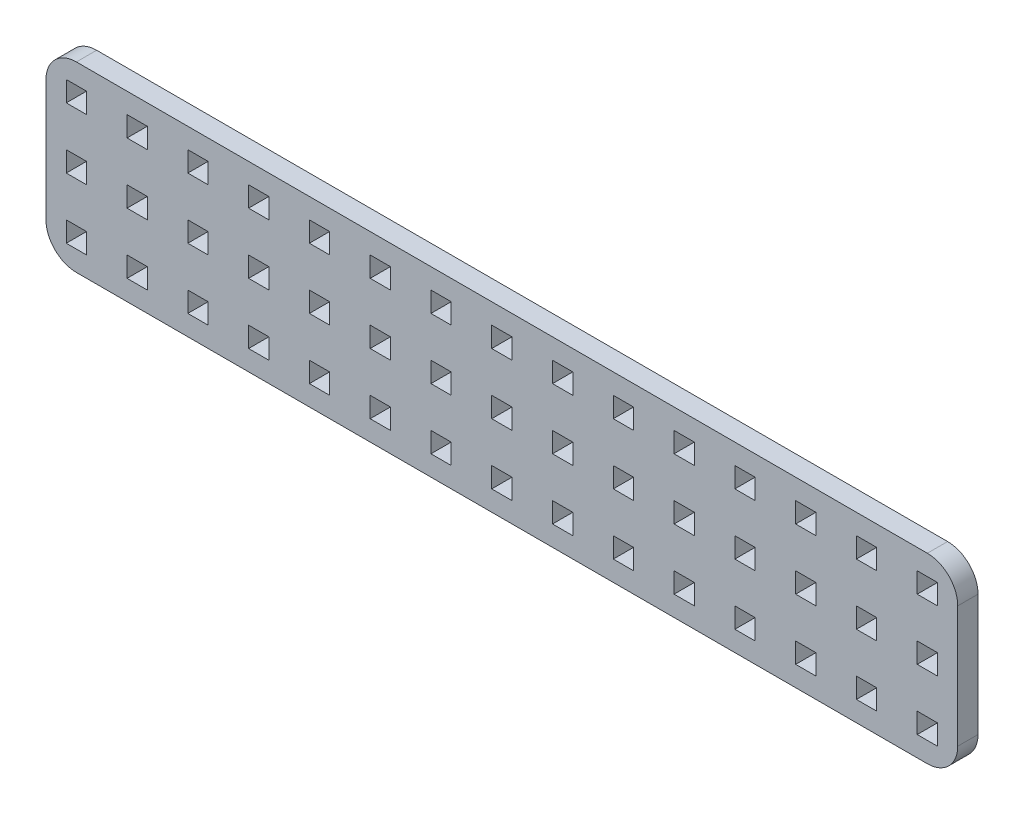
SolidWorks part; units mm, degrees
ref_plane "Alzado" through (0, 0, 0) normal (0, 0, 1) x (1, 0, 0)
ref_plane "Planta" through (0, 0, 0) normal (0, 1, 0) x (1, 0, 0)
ref_plane "Vista lateral" through (0, 0, 0) normal (1, 0, 0) x (0, 0, -1)
sketch "Model" plane through (0, 0, 0) normal (0, 0, 1) x (1, 0, 0)
  line L0 (7.8927, 294.0684) -> (7.8927, 291.0684)
  line L1 (10.8927, 294.0684) -> (7.8927, 294.0684)
  line L2 (10.8927, 291.0684) -> (10.8927, 294.0684)
  line L3 (7.8927, 291.0684) -> (10.8927, 291.0684)
  line L4 (16.8927, 294.0684) -> (16.8927, 291.0684)
  line L5 (19.8927, 294.0684) -> (16.8927, 294.0684)
  line L6 (19.8927, 291.0684) -> (19.8927, 294.0684)
  line L7 (16.8927, 291.0684) -> (19.8927, 291.0684)
  line L8 (25.8927, 294.0684) -> (25.8927, 291.0684)
  line L9 (28.8927, 294.0684) -> (25.8927, 294.0684)
  line L10 (28.8927, 291.0684) -> (28.8927, 294.0684)
  line L11 (25.8927, 291.0684) -> (28.8927, 291.0684)
  line L12 (34.8927, 294.0684) -> (34.8927, 291.0684)
  line L13 (37.8927, 294.0684) -> (34.8927, 294.0684)
  line L14 (37.8927, 291.0684) -> (37.8927, 294.0684)
  line L15 (34.8927, 291.0684) -> (37.8927, 291.0684)
  line L16 (43.8927, 294.0684) -> (43.8927, 291.0684)
  line L17 (46.8927, 294.0684) -> (43.8927, 294.0684)
  line L18 (46.8927, 291.0684) -> (46.8927, 294.0684)
  line L19 (43.8927, 291.0684) -> (46.8927, 291.0684)
  line L20 (52.8927, 294.0684) -> (52.8927, 291.0684)
  line L21 (55.8927, 294.0684) -> (52.8927, 294.0684)
  line L22 (55.8927, 291.0684) -> (55.8927, 294.0684)
  line L23 (52.8927, 291.0684) -> (55.8927, 291.0684)
  line L24 (61.8927, 294.0684) -> (61.8927, 291.0684)
  line L25 (64.8927, 294.0684) -> (61.8927, 294.0684)
  line L26 (64.8927, 291.0684) -> (64.8927, 294.0684)
  line L27 (61.8927, 291.0684) -> (64.8927, 291.0684)
  line L28 (70.8927, 294.0684) -> (70.8927, 291.0684)
  line L29 (73.8927, 294.0684) -> (70.8927, 294.0684)
  line L30 (73.8927, 291.0684) -> (73.8927, 294.0684)
  line L31 (70.8927, 291.0684) -> (73.8927, 291.0684)
  line L32 (79.8927, 294.0684) -> (79.8927, 291.0684)
  line L33 (82.8927, 294.0684) -> (79.8927, 294.0684)
  line L34 (82.8927, 291.0684) -> (82.8927, 294.0684)
  line L35 (79.8927, 291.0684) -> (82.8927, 291.0684)
  line L36 (88.8927, 294.0684) -> (88.8927, 291.0684)
  line L37 (91.8927, 294.0684) -> (88.8927, 294.0684)
  line L38 (91.8927, 291.0684) -> (91.8927, 294.0684)
  line L39 (88.8927, 291.0684) -> (91.8927, 291.0684)
  line L40 (97.8927, 294.0684) -> (97.8927, 291.0684)
  line L41 (100.8927, 294.0684) -> (97.8927, 294.0684)
  line L42 (100.8927, 291.0684) -> (100.8927, 294.0684)
  line L43 (97.8927, 291.0684) -> (100.8927, 291.0684)
  line L44 (106.8927, 294.0684) -> (106.8927, 291.0684)
  line L45 (109.8927, 294.0684) -> (106.8927, 294.0684)
  line L46 (109.8927, 291.0684) -> (109.8927, 294.0684)
  line L47 (106.8927, 291.0684) -> (109.8927, 291.0684)
  line L48 (115.8927, 294.0684) -> (115.8927, 291.0684)
  line L49 (118.8927, 294.0684) -> (115.8927, 294.0684)
  line L50 (118.8927, 291.0684) -> (118.8927, 294.0684)
  line L51 (115.8927, 291.0684) -> (118.8927, 291.0684)
  line L52 (124.8927, 294.0684) -> (124.8927, 291.0684)
  line L53 (127.8927, 294.0684) -> (124.8927, 294.0684)
  line L54 (127.8927, 291.0684) -> (127.8927, 294.0684)
  line L55 (124.8927, 291.0684) -> (127.8927, 291.0684)
  line L56 (133.8927, 294.0684) -> (133.8927, 291.0684)
  line L57 (136.8927, 294.0684) -> (133.8927, 294.0684)
  line L58 (136.8927, 291.0684) -> (136.8927, 294.0684)
  line L59 (133.8927, 291.0684) -> (136.8927, 291.0684)
  line L60 (7.8927, 285.0684) -> (7.8927, 282.0684)
  line L61 (10.8927, 285.0684) -> (7.8927, 285.0684)
  line L62 (10.8927, 282.0684) -> (10.8927, 285.0684)
  line L63 (7.8927, 282.0684) -> (10.8927, 282.0684)
  line L64 (16.8927, 285.0684) -> (16.8927, 282.0684)
  line L65 (19.8927, 285.0684) -> (16.8927, 285.0684)
  line L66 (19.8927, 282.0684) -> (19.8927, 285.0684)
  line L67 (16.8927, 282.0684) -> (19.8927, 282.0684)
  line L68 (25.8927, 285.0684) -> (25.8927, 282.0684)
  line L69 (28.8927, 285.0684) -> (25.8927, 285.0684)
  line L70 (28.8927, 282.0684) -> (28.8927, 285.0684)
  line L71 (25.8927, 282.0684) -> (28.8927, 282.0684)
  line L72 (34.8927, 285.0684) -> (34.8927, 282.0684)
  line L73 (37.8927, 285.0684) -> (34.8927, 285.0684)
  line L74 (37.8927, 282.0684) -> (37.8927, 285.0684)
  line L75 (34.8927, 282.0684) -> (37.8927, 282.0684)
  line L76 (43.8927, 285.0684) -> (43.8927, 282.0684)
  line L77 (46.8927, 285.0684) -> (43.8927, 285.0684)
  line L78 (46.8927, 282.0684) -> (46.8927, 285.0684)
  line L79 (43.8927, 282.0684) -> (46.8927, 282.0684)
  line L80 (52.8927, 285.0684) -> (52.8927, 282.0684)
  line L81 (55.8927, 285.0684) -> (52.8927, 285.0684)
  line L82 (55.8927, 282.0684) -> (55.8927, 285.0684)
  line L83 (52.8927, 282.0684) -> (55.8927, 282.0684)
  line L84 (61.8927, 285.0684) -> (61.8927, 282.0684)
  line L85 (64.8927, 285.0684) -> (61.8927, 285.0684)
  line L86 (64.8927, 282.0684) -> (64.8927, 285.0684)
  line L87 (61.8927, 282.0684) -> (64.8927, 282.0684)
  line L88 (70.8927, 285.0684) -> (70.8927, 282.0684)
  line L89 (73.8927, 285.0684) -> (70.8927, 285.0684)
  line L90 (73.8927, 282.0684) -> (73.8927, 285.0684)
  line L91 (70.8927, 282.0684) -> (73.8927, 282.0684)
  line L92 (79.8927, 285.0684) -> (79.8927, 282.0684)
  line L93 (82.8927, 285.0684) -> (79.8927, 285.0684)
  line L94 (82.8927, 282.0684) -> (82.8927, 285.0684)
  line L95 (79.8927, 282.0684) -> (82.8927, 282.0684)
  line L96 (88.8927, 285.0684) -> (88.8927, 282.0684)
  line L97 (91.8927, 285.0684) -> (88.8927, 285.0684)
  line L98 (91.8927, 282.0684) -> (91.8927, 285.0684)
  line L99 (88.8927, 282.0684) -> (91.8927, 282.0684)
  line L100 (97.8927, 285.0684) -> (97.8927, 282.0684)
  line L101 (100.8927, 285.0684) -> (97.8927, 285.0684)
  line L102 (100.8927, 282.0684) -> (100.8927, 285.0684)
  line L103 (97.8927, 282.0684) -> (100.8927, 282.0684)
  line L104 (106.8927, 285.0684) -> (106.8927, 282.0684)
  line L105 (109.8927, 285.0684) -> (106.8927, 285.0684)
  line L106 (109.8927, 282.0684) -> (109.8927, 285.0684)
  line L107 (106.8927, 282.0684) -> (109.8927, 282.0684)
  line L108 (115.8927, 285.0684) -> (115.8927, 282.0684)
  line L109 (118.8927, 285.0684) -> (115.8927, 285.0684)
  line L110 (118.8927, 282.0684) -> (118.8927, 285.0684)
  line L111 (115.8927, 282.0684) -> (118.8927, 282.0684)
  line L112 (124.8927, 285.0684) -> (124.8927, 282.0684)
  line L113 (127.8927, 285.0684) -> (124.8927, 285.0684)
  line L114 (127.8927, 282.0684) -> (127.8927, 285.0684)
  line L115 (124.8927, 282.0684) -> (127.8927, 282.0684)
  line L116 (133.8927, 285.0684) -> (133.8927, 282.0684)
  line L117 (136.8927, 285.0684) -> (133.8927, 285.0684)
  line L118 (136.8927, 282.0684) -> (136.8927, 285.0684)
  line L119 (133.8927, 282.0684) -> (136.8927, 282.0684)
  line L120 (7.8927, 276.0684) -> (7.8927, 273.0684)
  line L121 (10.8927, 276.0684) -> (7.8927, 276.0684)
  line L122 (10.8927, 273.0684) -> (10.8927, 276.0684)
  line L123 (7.8927, 273.0684) -> (10.8927, 273.0684)
  line L124 (16.8927, 276.0684) -> (16.8927, 273.0684)
  line L125 (19.8927, 276.0684) -> (16.8927, 276.0684)
  line L126 (19.8927, 273.0684) -> (19.8927, 276.0684)
  line L127 (16.8927, 273.0684) -> (19.8927, 273.0684)
  line L128 (25.8927, 276.0684) -> (25.8927, 273.0684)
  line L129 (28.8927, 276.0684) -> (25.8927, 276.0684)
  line L130 (28.8927, 273.0684) -> (28.8927, 276.0684)
  line L131 (25.8927, 273.0684) -> (28.8927, 273.0684)
  line L132 (34.8927, 276.0684) -> (34.8927, 273.0684)
  line L133 (37.8927, 276.0684) -> (34.8927, 276.0684)
  line L134 (37.8927, 273.0684) -> (37.8927, 276.0684)
  line L135 (34.8927, 273.0684) -> (37.8927, 273.0684)
  line L136 (43.8927, 276.0684) -> (43.8927, 273.0684)
  line L137 (46.8927, 276.0684) -> (43.8927, 276.0684)
  line L138 (46.8927, 273.0684) -> (46.8927, 276.0684)
  line L139 (43.8927, 273.0684) -> (46.8927, 273.0684)
  line L140 (52.8927, 276.0684) -> (52.8927, 273.0684)
  line L141 (55.8927, 276.0684) -> (52.8927, 276.0684)
  line L142 (55.8927, 273.0684) -> (55.8927, 276.0684)
  line L143 (52.8927, 273.0684) -> (55.8927, 273.0684)
  line L144 (61.8927, 276.0684) -> (61.8927, 273.0684)
  line L145 (64.8927, 276.0684) -> (61.8927, 276.0684)
  line L146 (64.8927, 273.0684) -> (64.8927, 276.0684)
  line L147 (61.8927, 273.0684) -> (64.8927, 273.0684)
  line L148 (70.8927, 276.0684) -> (70.8927, 273.0684)
  line L149 (73.8927, 276.0684) -> (70.8927, 276.0684)
  line L150 (73.8927, 273.0684) -> (73.8927, 276.0684)
  line L151 (70.8927, 273.0684) -> (73.8927, 273.0684)
  line L152 (79.8927, 276.0684) -> (79.8927, 273.0684)
  line L153 (82.8927, 276.0684) -> (79.8927, 276.0684)
  line L154 (82.8927, 273.0684) -> (82.8927, 276.0684)
  line L155 (79.8927, 273.0684) -> (82.8927, 273.0684)
  line L156 (88.8927, 276.0684) -> (88.8927, 273.0684)
  line L157 (91.8927, 276.0684) -> (88.8927, 276.0684)
  line L158 (91.8927, 273.0684) -> (91.8927, 276.0684)
  line L159 (88.8927, 273.0684) -> (91.8927, 273.0684)
  line L160 (97.8927, 276.0684) -> (97.8927, 273.0684)
  line L161 (100.8927, 276.0684) -> (97.8927, 276.0684)
  line L162 (100.8927, 273.0684) -> (100.8927, 276.0684)
  line L163 (97.8927, 273.0684) -> (100.8927, 273.0684)
  line L164 (106.8927, 276.0684) -> (106.8927, 273.0684)
  line L165 (109.8927, 276.0684) -> (106.8927, 276.0684)
  line L166 (109.8927, 273.0684) -> (109.8927, 276.0684)
  line L167 (106.8927, 273.0684) -> (109.8927, 273.0684)
  line L168 (115.8927, 276.0684) -> (115.8927, 273.0684)
  line L169 (118.8927, 276.0684) -> (115.8927, 276.0684)
  line L170 (118.8927, 273.0684) -> (118.8927, 276.0684)
  line L171 (115.8927, 273.0684) -> (118.8927, 273.0684)
  line L172 (124.8927, 276.0684) -> (124.8927, 273.0684)
  line L173 (127.8927, 276.0684) -> (124.8927, 276.0684)
  line L174 (127.8927, 273.0684) -> (127.8927, 276.0684)
  line L175 (124.8927, 273.0684) -> (127.8927, 273.0684)
  line L176 (133.8927, 276.0684) -> (133.8927, 273.0684)
  line L177 (136.8927, 276.0684) -> (133.8927, 276.0684)
  line L178 (136.8927, 273.0684) -> (136.8927, 276.0684)
  line L179 (133.8927, 273.0684) -> (136.8927, 273.0684)
  line L180 (139.8927, 274.5711) -> (139.8927, 292.5684)
  line L181 (135.3927, 297.0684) -> (9.3927, 297.0684)
  line L182 (4.8927, 292.5684) -> (4.8927, 274.5711)
  line L183 (9.3927, 270.0711) -> (135.3927, 270.0711)
  arc A0 (139.8927, 292.5684) -> (135.3927, 297.0684) centre (135.3927, 292.5684) ccw
  arc A1 (135.3927, 270.0711) -> (139.8927, 274.5711) centre (135.3927, 274.5711) ccw
  arc A2 (9.3927, 297.0684) -> (4.8927, 292.5684) centre (9.3927, 292.5684) ccw
  arc A3 (4.8927, 274.5711) -> (9.3927, 270.0711) centre (9.3927, 274.5711) ccw
extrude "Saliente-Extruir1" add sketch "Model" along normal blind 3
